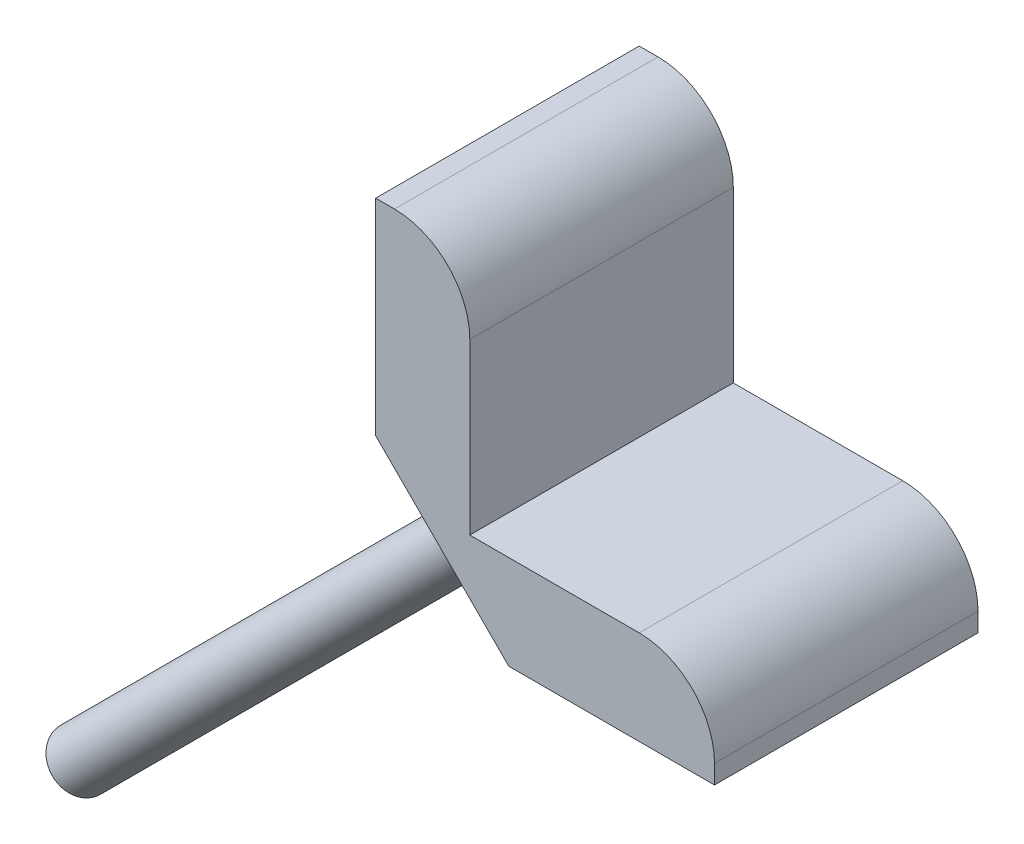
SolidWorks part; units mm, degrees
ref_plane "Front Plane" through (0, 0, 0) normal (0, 0, 1) x (1, 0, 0)
ref_plane "Top Plane" through (0, 0, 0) normal (0, 1, 0) x (1, 0, 0)
ref_plane "Right Plane" through (0, 0, 0) normal (1, 0, 0) x (0, 0, -1)
sketch "Sketch1" plane through (0, 0, 0) normal (0, 1, 0) x (1, 0, 0)
  line L1 (0, 0) -> (-90, 0)
  line L2 (0, 0) -> (0, 80)
  line L3 (0, 80) -> (-90, 80)
  line L4 (-90, 0) -> (-90, 80)
  dimension "D1" = 80
  dimension "D2" = 90
extrude "Boss-Extrude1" add sketch "Sketch1" along normal blind 90 contours L2 L1 L4 L3
sketch "Sketch2" plane through (0, 0, -80) normal (0, 0, -1) x (-1, 0, 0)
  line L0 (0, 90) -> (0, 0) construction
  line L1 (0, 25) -> (65, 25)
  line L2 (0, 25) -> (0, 90)
  line L3 (0, 90) -> (65, 90)
  line L4 (65, 25) -> (65, 90)
  line L5 (0, 90) -> (90, 90) construction
  dimension "D1" = 65
  dimension "D2" = 65
extrude "Cut-Extrude1" cut sketch "Sketch2" against normal blind 100
fillet "Fillet1" radius 20 2 edges at (0, 25, -40) (-65, 90, -40)
sketch "Sketch3" plane through (0, 0, -80) normal (0, 0, -1) x (-1, 0, 0)
  line L0 (54.6447, 0) -> (90, 35.3553)
  line L1 (0, 0) -> (90, 0) construction
  line L2 (90, 90) -> (90, 0) construction
  line L3 (54.6447, 0) -> (90, 0)
  line L4 (90, 0) -> (90, 35.3553)
  dimension "D1" = 50
extrude "Cut-Extrude2" cut sketch "Sketch3" against normal blind 100
sketch "Sketch4" plane through (-27.3223, -27.3223, 0) normal (-0.7071, -0.7071, 0) x (0, 0, 1)
  line L0 (-80, 88.6396) -> (-80, 38.6396) construction
  line L1 (0, 38.6396) -> (0, 88.6396) construction
  line L2 (0, 88.6396) -> (-80, 88.6396) construction
  line L3 (-80, 38.6396) -> (0, 38.6396) construction
  circle A0 centre (-60, 63.6396) radius 7.5
  circle A1 centre (-20, 63.6396) radius 7.5
  point P10 (0, 0)
  dimension "D1" = 15
  dimension "D2" = 15
  dimension "D3" = 20
  dimension "D4" = 20
  dimension "D5" = 25
  dimension "D6" = 25
extrude "Boss-Extrude2" add sketch "Sketch4" along normal blind 150
sketch "Sketch6" plane through (-27.3223, -27.3223, 0) normal (-0.7071, -0.7071, 0) x (0, 0, 1)
  line L0 (0, 127.2792) -> (-80, 127.2792) construction
  line L1 (-10, 127.2792) -> (0, 127.2792)
  line L2 (-10, 127.2792) -> (-10, 0)
  line L3 (-10, 0) -> (0, 0)
  line L4 (0, 127.2792) -> (0, 0)
  dimension "D1" = 10
extrude "Cut-Extrude4" cut sketch "Sketch6" against normal through all
